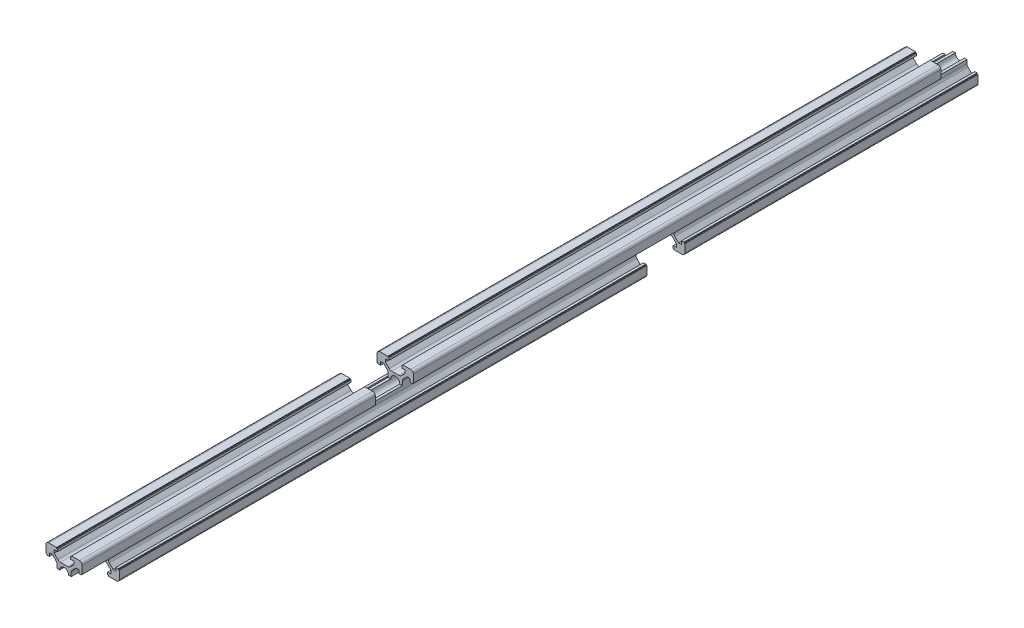
SolidWorks part; units mm, degrees
material "6063-O"
ref_plane "Front Plane" through (0, 0, 0) normal (0, 0, 1) x (1, 0, 0)
ref_plane "Top Plane" through (0, 0, 0) normal (0, 1, 0) x (1, 0, 0)
ref_plane "Right Plane" through (0, 0, 0) normal (1, 0, 0) x (0, 0, -1)
sketch "Sketch1" plane through (0, 0, 0) normal (0, 0, 1) x (1, 0, 0)
  line L0 (10, -4.1) -> (10, -8.5)
  line L1 (4.1, 10) -> (8.5, 10)
  line L2 (8.5, -10) -> (4.1, -10)
  line L3 (-8.5, -10) -> (-4.1, -10)
  line L4 (10, 8.5) -> (10, 4.1)
  line L7 (8.5, 10) -> (4.1, 10)
  line L8 (5.5, 6.5607) -> (3.4251, 4.4858)
  line L9 (8.5, 10) -> (4.1, 10)
  line L10 (3.9, 2.0109) -> (3.9, -2.0109)
  line L11 (2.0109, -3.9) -> (-2.0109, -3.9)
  line L12 (-3.9, -2.0109) -> (-3.9, 2.0109)
  line L13 (-2.0109, 3.9) -> (2.8393, 3.9)
  line L14 (2.5, 0) -> (22.2403, 0) construction
  line L15 (3.6, 9.5) -> (3.6, 8.2)
  line L16 (9.5, 3.6) -> (8.2, 3.6)
  line L17 (8.2, 3.6) -> (8.2, 5.5)
  line L18 (8.2, 5.5) -> (6.5607, 5.5)
  line L19 (10, -4.1) -> (10, -8.5)
  line L20 (4.1, 9.5) -> (3.6, 9.5)
  line L21 (4.1, 10) -> (4.1, 9.5)
  line L22 (8.5, 10) -> (4.1, 10)
  line L23 (10, 4.1) -> (9.5, 4.1)
  line L24 (9.5, 4.1) -> (9.5, 3.6)
  line L25 (5.5, 8.2) -> (5.5, 6.5607)
  line L26 (3.6, 8.2) -> (5.5, 8.2)
  line L27 (4.4858, 3.4251) -> (6.5607, 5.5)
  line L28 (10, -8.5) -> (10, -4.1)
  line L29 (6.5607, -5.5) -> (4.4858, -3.4251)
  line L30 (10, -8.5) -> (10, -4.1)
  line L31 (2.0109, -3.9) -> (-2.0109, -3.9)
  line L32 (3.9, 2.8393) -> (3.9, -2.0109)
  line L33 (9.5, -3.6) -> (8.2, -3.6)
  line L34 (3.6, -9.5) -> (3.6, -8.2)
  line L35 (3.6, -8.2) -> (5.5, -8.2)
  line L36 (5.5, -8.2) -> (5.5, -6.5607)
  line L37 (9.5, -4.1) -> (9.5, -3.6)
  line L38 (10, -4.1) -> (9.5, -4.1)
  line L39 (10, -8.5) -> (10, -4.1)
  line L40 (4.1, -10) -> (4.1, -9.5)
  line L41 (4.1, -9.5) -> (3.6, -9.5)
  line L42 (8.2, -5.5) -> (6.5607, -5.5)
  line L43 (8.2, -3.6) -> (8.2, -5.5)
  line L44 (3.4251, -4.4858) -> (5.5, -6.5607)
  line L45 (-4.1, -10) -> (-8.5, -10)
  line L46 (-10, -8.5) -> (-10, -4.1)
  line L47 (-8.5, -10) -> (-4.1, -10)
  line L48 (-5.5, -6.5607) -> (-3.4251, -4.4858)
  line L49 (-8.5, -10) -> (-4.1, -10)
  line L50 (-3.9, -2.0109) -> (-3.9, 2.0109)
  line L51 (2.0109, -3.9) -> (-2.0109, -3.9)
  line L52 (-3.6, -9.5) -> (-3.6, -8.2)
  line L53 (-9.5, -3.6) -> (-8.2, -3.6)
  line L54 (-8.2, -3.6) -> (-8.2, -5.5)
  line L55 (-8.2, -5.5) -> (-6.5607, -5.5)
  line L56 (-4.1, -9.5) -> (-3.6, -9.5)
  line L57 (-4.1, -10) -> (-4.1, -9.5)
  line L58 (-8.5, -10) -> (-4.1, -10)
  line L59 (-10, -4.1) -> (-9.5, -4.1)
  line L60 (-9.5, -4.1) -> (-9.5, -3.6)
  line L61 (-5.5, -8.2) -> (-5.5, -6.5607)
  line L62 (-3.6, -8.2) -> (-5.5, -8.2)
  line L63 (-4.4858, -3.4251) -> (-6.5607, -5.5)
  line L64 (-10, 4.1) -> (-10, 8.5)
  line L65 (-8.5, 10) -> (-4.1, 10)
  line L66 (-10, 8.5) -> (-10, 4.1)
  line L67 (-6.5607, 5.5) -> (-4.4858, 3.4251)
  line L68 (-10, 8.5) -> (-10, 4.1)
  line L69 (-2.0109, 3.9) -> (2.0109, 3.9)
  line L70 (-3.9, -2.0109) -> (-3.9, 2.0109)
  line L71 (-9.5, 3.6) -> (-8.2, 3.6)
  line L72 (-3.6, 9.5) -> (-3.6, 8.2)
  line L73 (-3.6, 8.2) -> (-5.5, 8.2)
  line L74 (-5.5, 8.2) -> (-5.5, 6.5607)
  line L75 (-9.5, 4.1) -> (-9.5, 3.6)
  line L76 (-10, 4.1) -> (-9.5, 4.1)
  line L77 (-10, 8.5) -> (-10, 4.1)
  line L78 (-4.1, 10) -> (-4.1, 9.5)
  line L79 (-4.1, 9.5) -> (-3.6, 9.5)
  line L80 (-8.2, 5.5) -> (-6.5607, 5.5)
  line L81 (-8.2, 3.6) -> (-8.2, 5.5)
  line L82 (-3.4251, 4.4858) -> (-5.5, 6.5607)
  line L83 (4.1, -10) -> (8.5, -10)
  arc A0 (2.0109, -3.9) -> (3.4251, -4.4858) centre (2.0109, -5.9) cw
  arc A1 (4.4858, -3.4251) -> (3.9, -2.0109) centre (5.9, -2.0109) cw
  arc A2 (3.9, 2.0109) -> (4.4858, 3.4251) centre (5.9, 2.0109) cw
  arc A3 (2.0109, 3.9) -> (3.4251, 4.4858) centre (2.0109, 5.9) ccw
  arc A4 (-2.0109, 3.9) -> (-3.4251, 4.4858) centre (-2.0109, 5.9) cw
  arc A5 (-4.4858, 3.4251) -> (-3.9, 2.0109) centre (-5.9, 2.0109) cw
  arc A6 (-3.4251, -4.4858) -> (-2.0109, -3.9) centre (-2.0109, -5.9) cw
  arc A7 (-3.9, -2.0109) -> (-4.4858, -3.4251) centre (-5.9, -2.0109) cw
  circle A8 centre (0, 0) radius 2.5
  arc A9 (-8.5, -10) -> (-10, -8.5) centre (-8.5, -8.5) cw
  arc A10 (-10, 8.5) -> (-8.5, 10) centre (-8.5, 8.5) cw
  arc A11 (8.5, 10) -> (10, 8.5) centre (8.5, 8.5) cw
  arc A12 (8.5, -10) -> (10, -8.5) centre (8.5, -8.5) ccw
  point P0 (0, 0)
  point P86 (0, 0)
  point P107 (10, -10)
  dimension "D3" = 2
  dimension "D5" = 5
  dimension "D2" = 1.5
  dimension "D8" = 1.5
  dimension "D6" = 4
  dimension "D7" = 6.1
  dimension "D11" = 0.5
  dimension "D12" = 0.5
extrude "Boss-Extrude2" add sketch "Sketch1" along normal blind 495
sketch "ｽｹｯﾁ1" plane through (-10, 0, 0) normal (-1, 0, 0) x (0, 0, 1)
  line L0 (495, 10) -> (0, 10) construction
  line L10 (247.5, 10) -> (247.5, -66.4608) construction
  line L20 (183, 0) -> (162, 0)
  line L21 (183, 0) -> (183, -10)
  line L22 (183, -10) -> (162, -10)
  line L23 (162, 0) -> (162, -10)
  line L24 (0, 0) -> (20.5, 0)
  line L25 (0, 0) -> (0, 10)
  line L26 (0, 10) -> (20.5, 10)
  line L27 (20.5, 0) -> (20.5, 10)
  line L39 (474.5, 0) -> (495, 0)
  line L40 (474.5, 0) -> (474.5, -10)
  line L41 (474.5, -10) -> (495, -10)
  line L42 (495, 0) -> (495, -10)
  line L43 (312, 0) -> (333, 0)
  line L44 (312, 0) -> (312, 10)
  line L45 (312, 10) -> (333, 10)
  line L46 (333, 0) -> (333, 10)
  dimension "D1" = 64.5
  dimension "D2" = 21
extrude "ｶｯﾄ - 押し出し1" cut sketch "ｽｹｯﾁ1" against normal through all
